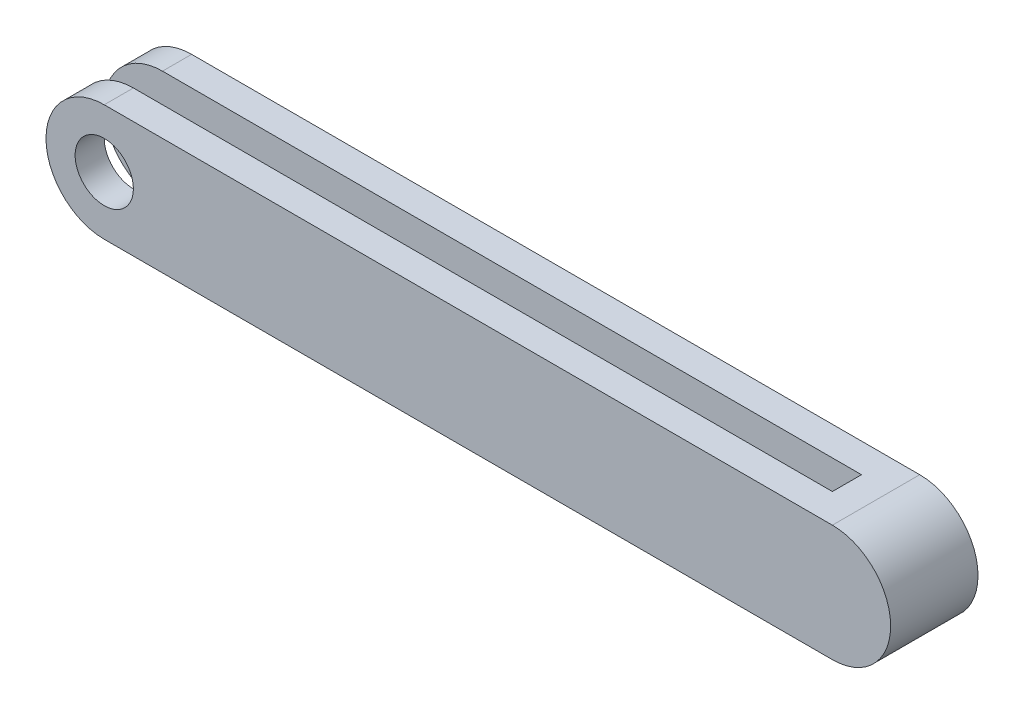
SolidWorks part; units mm, degrees
ref_plane "Alzado" through (0, 0, 0) normal (0, 0, 1) x (1, 0, 0)
ref_plane "Planta" through (0, 0, 0) normal (0, 1, 0) x (1, 0, 0)
ref_plane "Vista lateral" through (0, 0, 0) normal (1, 0, 0) x (0, 0, -1)
sketch "Croquis1" plane through (0, 0, 0) normal (0, 0, 1) x (1, 0, 0)
  line L0 (0, 0) -> (125, 0) construction
  line L1 (0, 10) -> (125, 10)
  line L2 (0, -10) -> (125, -10)
  circle A0 centre (0, 0) radius 5
  arc A1 (0, 10) -> (0, -10) centre (0, 0) ccw
  arc A2 (125, -10) -> (125, 10) centre (125, 0) ccw
  point P3 (62.5, 0)
  dimension "D1" = 10
  dimension "D2" = 10
  dimension "D3" = 125
extrude "Saliente-Extruir1" add sketch "Croquis1" along normal blind 15
sketch "Croquis2" plane through (0, 10, 0) normal (0, 1, 0) x (1, 0, 0)
  line L0 (-10, -5) -> (-10, -10)
  line L1 (-10, 0) -> (-10, -15) construction
  line L2 (-10, -10) -> (120, -10)
  line L3 (120, -10) -> (120, -5)
  line L4 (120, -5) -> (-10, -5)
  line L5 (125, 0) -> (0, 0) construction
  dimension "D1" = 5
  dimension "D2" = 130
  dimension "D3" = 5
extrude "Cortar-Extruir1" cut sketch "Croquis2" against normal through all
